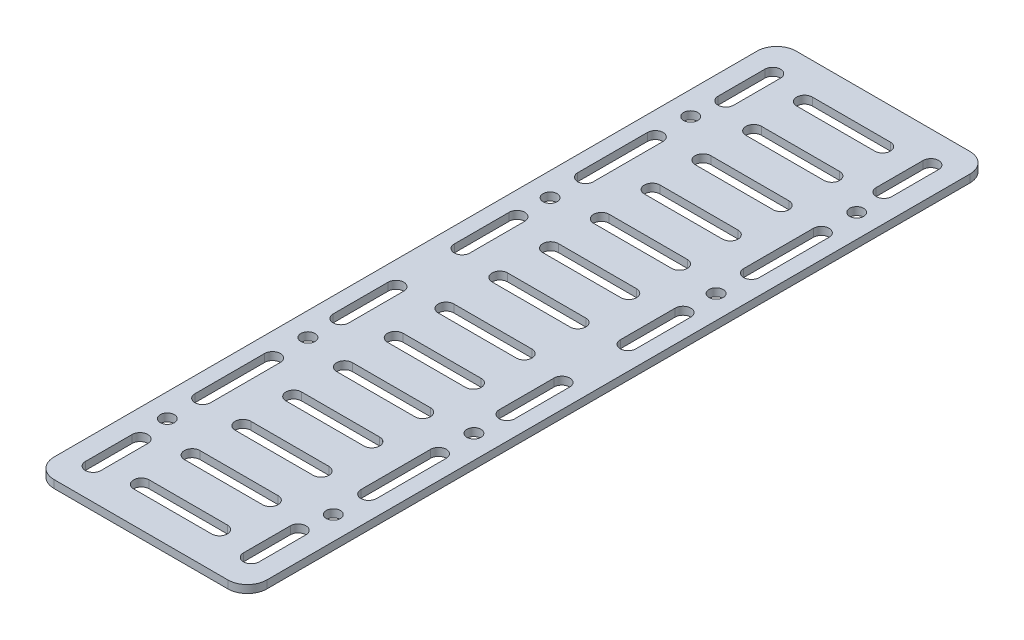
SolidWorks part; units mm, degrees
ref_plane "Front Plane" through (0, 0, 0) normal (0, 0, 1) x (1, 0, 0)
ref_plane "Top Plane" through (0, 0, 0) normal (0, 1, 0) x (1, 0, 0)
ref_plane "Right Plane" through (0, 0, 0) normal (1, 0, 0) x (0, 0, -1)
sketch "Sketch1" plane through (0, 0, 0) normal (0, 1, 0) x (1, 0, 0)
  line L1 (-27.25, 95) -> (27.25, 95)
  line L2 (-27.25, 95) -> (-27.25, -95)
  line L3 (-27.25, -95) -> (27.25, -95)
  line L4 (27.25, 95) -> (27.25, -95)
  line L5 (-27.25, 95) -> (27.25, -95) construction
  line L6 (-27.25, -95) -> (27.25, 95) construction
  point P0 (0, 0)
  dimension "D1" = 54.5
  dimension "D2" = 190
extrude "Boss-Extrude1" add sketch "Sketch1" along normal blind 2
hole_wizard "M3 Clearance Hole1" positions "Sketch3" profile "Sketch4" hole size "M3" standard "ANSI Metric" end condition through all
sketch "Sketch3" plane through (0, 2, 0) normal (0, 1, 0) x (1, 0, 0)
  line L0 (0, 0) -> (0, 100.7242) construction
  line L2 (0, 0) -> (-58.9219, 0) construction
  line L4 (-27.25, 95) -> (-27.25, -95) construction
  point P0 (-21.25, 67)
  point P15 (-21.25, 31)
  point P17 (21.25, 67)
  point P18 (21.25, 31)
  point P20 (21.25, -31)
  point P21 (21.25, -67)
  point P22 (-21.25, -67)
  point P23 (-21.25, -31)
  dimension "D1" = 6
  dimension "D2" = 31
  dimension "D3" = 36
sketch "Sketch4" plane through (-21.25, 2, -67) normal (1, 0, 0) x (0, 0, 1)
  line L0 (0, 0) -> (0, 2)
  line L1 (0, 2) -> (1.8, 2)
  line L2 (1.8, 2) -> (1.8, 0)
  line L5 (1.8, 0) -> (0, 0)
  line L11 (0, -6.35) -> (0, 107.95) construction
  dimension "Thru Hole Dia." = 3.6
  dimension "Thru Hole Depth" = 2
sketch "Sketch5" plane through (0, 2, 0) normal (0, 1, 0) x (1, 0, 0)
  line L0 (-20.25, 87) -> (-20.25, 75) construction
  line L1 (-18.25, 87) -> (-18.25, 75)
  line L2 (-22.25, 87) -> (-22.25, 75)
  line L3 (0, 0) -> (0, 101.9957) construction
  line L4 (20.25, 87) -> (20.25, 75) construction
  line L5 (18.25, 87) -> (18.25, 75)
  line L6 (22.25, 87) -> (22.25, 75)
  line L11 (-10, 84.8852) -> (10, 84.8852) construction
  line L12 (-10, 86.8852) -> (10, 86.8852)
  line L13 (-10, 82.8852) -> (10, 82.8852)
  line L14 (-10, 71.8852) -> (10, 71.8852) construction
  line L15 (-10, 73.8852) -> (10, 73.8852)
  line L16 (-10, 69.8852) -> (10, 69.8852)
  line L17 (-10, 58.8852) -> (10, 58.8852) construction
  line L18 (-10, 60.8852) -> (10, 60.8852)
  line L19 (-10, 56.8852) -> (10, 56.8852)
  line L20 (-10, 45.8852) -> (10, 45.8852) construction
  line L21 (-10, 47.8852) -> (10, 47.8852)
  line L22 (-10, 43.8852) -> (10, 43.8852)
  line L23 (-10, 32.8852) -> (10, 32.8852) construction
  line L24 (-10, 34.8852) -> (10, 34.8852)
  line L25 (-10, 30.8852) -> (10, 30.8852)
  line L26 (-10, 19.8852) -> (10, 19.8852) construction
  line L27 (-10, 21.8852) -> (10, 21.8852)
  line L28 (-10, 17.8852) -> (10, 17.8852)
  line L29 (-10, 6.8852) -> (10, 6.8852) construction
  line L30 (-10, 8.8852) -> (10, 8.8852)
  line L31 (-10, 4.8852) -> (10, 4.8852)
  line L32 (-21.25, 67) -> (-21.25, 31) construction
  line L33 (-21.25, 57.9327) -> (-21.25, 40.0673) construction
  line L34 (-19.25, 57.9327) -> (-19.25, 40.0673)
  line L35 (-23.25, 57.9327) -> (-23.25, 40.0673)
  line L36 (-21.25, 31) -> (-21.25, 0) construction
  line L37 (-21.25, 22.5337) -> (-21.25, 8.4663) construction
  line L38 (-19.25, 22.5337) -> (-19.25, 8.4663)
  line L39 (-23.25, 22.5337) -> (-23.25, 8.4663)
  line L40 (21.25, 57.9327) -> (21.25, 40.0673) construction
  line L41 (19.25, 57.9327) -> (19.25, 40.0673)
  line L42 (23.25, 57.9327) -> (23.25, 40.0673)
  line L43 (21.25, 22.5337) -> (21.25, 8.4663) construction
  line L44 (19.25, 22.5337) -> (19.25, 8.4663)
  line L45 (23.25, 22.5337) -> (23.25, 8.4663)
  line L46 (0, 0) -> (46.6314, 0) construction
  line L47 (-20.25, -87) -> (-20.25, -75) construction
  line L48 (-18.25, -87) -> (-18.25, -75)
  line L49 (-22.25, -87) -> (-22.25, -75)
  line L50 (20.25, -87) -> (20.25, -75) construction
  line L51 (18.25, -87) -> (18.25, -75)
  line L52 (22.25, -87) -> (22.25, -75)
  line L56 (-10, -84.8852) -> (10, -84.8852) construction
  line L57 (-10, -86.8852) -> (10, -86.8852)
  line L58 (-10, -82.8852) -> (10, -82.8852)
  line L59 (-10, -71.8852) -> (10, -71.8852) construction
  line L60 (-10, -73.8852) -> (10, -73.8852)
  line L61 (-10, -69.8852) -> (10, -69.8852)
  line L62 (-10, -58.8852) -> (10, -58.8852) construction
  line L63 (-10, -60.8852) -> (10, -60.8852)
  line L64 (-10, -56.8852) -> (10, -56.8852)
  line L65 (-10, -45.8852) -> (10, -45.8852) construction
  line L66 (-10, -47.8852) -> (10, -47.8852)
  line L67 (-10, -43.8852) -> (10, -43.8852)
  line L68 (-10, -32.8852) -> (10, -32.8852) construction
  line L69 (-10, -34.8852) -> (10, -34.8852)
  line L70 (-10, -30.8852) -> (10, -30.8852)
  line L71 (-10, -19.8852) -> (10, -19.8852) construction
  line L72 (-10, -21.8852) -> (10, -21.8852)
  line L73 (-10, -17.8852) -> (10, -17.8852)
  line L74 (-10, -6.8852) -> (10, -6.8852) construction
  line L75 (-10, -8.8852) -> (10, -8.8852)
  line L76 (-10, -4.8852) -> (10, -4.8852)
  line L77 (-21.25, -57.9327) -> (-21.25, -40.0673) construction
  line L78 (-19.25, -57.9327) -> (-19.25, -40.0673)
  line L79 (-23.25, -57.9327) -> (-23.25, -40.0673)
  line L80 (-21.25, -22.5337) -> (-21.25, -8.4663) construction
  line L81 (-19.25, -22.5337) -> (-19.25, -8.4663)
  line L82 (-23.25, -22.5337) -> (-23.25, -8.4663)
  line L83 (21.25, -57.9327) -> (21.25, -40.0673) construction
  line L84 (19.25, -57.9327) -> (19.25, -40.0673)
  line L85 (23.25, -57.9327) -> (23.25, -40.0673)
  line L86 (21.25, -22.5337) -> (21.25, -8.4663) construction
  line L87 (19.25, -22.5337) -> (19.25, -8.4663)
  line L88 (23.25, -22.5337) -> (23.25, -8.4663)
  arc A0 (-18.25, 87) -> (-22.25, 87) centre (-20.25, 87) ccw
  arc A1 (-22.25, 75) -> (-18.25, 75) centre (-20.25, 75) ccw
  arc A2 (18.25, 87) -> (22.25, 87) centre (20.25, 87) cw
  arc A3 (22.25, 75) -> (18.25, 75) centre (20.25, 75) cw
  arc A6 (-10, 86.8852) -> (-10, 82.8852) centre (-10, 84.8852) ccw
  arc A7 (10, 82.8852) -> (10, 86.8852) centre (10, 84.8852) ccw
  arc A8 (-10, 73.8852) -> (-10, 69.8852) centre (-10, 71.8852) ccw
  arc A9 (10, 69.8852) -> (10, 73.8852) centre (10, 71.8852) ccw
  arc A10 (-10, 60.8852) -> (-10, 56.8852) centre (-10, 58.8852) ccw
  arc A11 (10, 56.8852) -> (10, 60.8852) centre (10, 58.8852) ccw
  arc A12 (-10, 47.8852) -> (-10, 43.8852) centre (-10, 45.8852) ccw
  arc A13 (10, 43.8852) -> (10, 47.8852) centre (10, 45.8852) ccw
  arc A14 (-10, 34.8852) -> (-10, 30.8852) centre (-10, 32.8852) ccw
  arc A15 (10, 30.8852) -> (10, 34.8852) centre (10, 32.8852) ccw
  arc A16 (-10, 21.8852) -> (-10, 17.8852) centre (-10, 19.8852) ccw
  arc A17 (10, 17.8852) -> (10, 21.8852) centre (10, 19.8852) ccw
  arc A18 (-10, 8.8852) -> (-10, 4.8852) centre (-10, 6.8852) ccw
  arc A19 (10, 4.8852) -> (10, 8.8852) centre (10, 6.8852) ccw
  arc A20 (-19.25, 57.9327) -> (-23.25, 57.9327) centre (-21.25, 57.9327) ccw
  arc A21 (-23.25, 40.0673) -> (-19.25, 40.0673) centre (-21.25, 40.0673) ccw
  arc A22 (-19.25, 22.5337) -> (-23.25, 22.5337) centre (-21.25, 22.5337) ccw
  arc A23 (-23.25, 8.4663) -> (-19.25, 8.4663) centre (-21.25, 8.4663) ccw
  arc A24 (19.25, 57.9327) -> (23.25, 57.9327) centre (21.25, 57.9327) cw
  arc A25 (23.25, 40.0673) -> (19.25, 40.0673) centre (21.25, 40.0673) cw
  arc A26 (19.25, 22.5337) -> (23.25, 22.5337) centre (21.25, 22.5337) cw
  arc A27 (23.25, 8.4663) -> (19.25, 8.4663) centre (21.25, 8.4663) cw
  arc A28 (-18.25, -87) -> (-22.25, -87) centre (-20.25, -87) cw
  arc A29 (-22.25, -75) -> (-18.25, -75) centre (-20.25, -75) cw
  arc A30 (18.25, -87) -> (22.25, -87) centre (20.25, -87) ccw
  arc A31 (22.25, -75) -> (18.25, -75) centre (20.25, -75) ccw
  arc A34 (-10, -86.8852) -> (-10, -82.8852) centre (-10, -84.8852) cw
  arc A35 (10, -82.8852) -> (10, -86.8852) centre (10, -84.8852) cw
  arc A36 (-10, -73.8852) -> (-10, -69.8852) centre (-10, -71.8852) cw
  arc A37 (10, -69.8852) -> (10, -73.8852) centre (10, -71.8852) cw
  arc A38 (-10, -60.8852) -> (-10, -56.8852) centre (-10, -58.8852) cw
  arc A39 (10, -56.8852) -> (10, -60.8852) centre (10, -58.8852) cw
  arc A40 (-10, -47.8852) -> (-10, -43.8852) centre (-10, -45.8852) cw
  arc A41 (10, -43.8852) -> (10, -47.8852) centre (10, -45.8852) cw
  arc A42 (-10, -34.8852) -> (-10, -30.8852) centre (-10, -32.8852) cw
  arc A43 (10, -30.8852) -> (10, -34.8852) centre (10, -32.8852) cw
  arc A44 (-10, -21.8852) -> (-10, -17.8852) centre (-10, -19.8852) cw
  arc A45 (10, -17.8852) -> (10, -21.8852) centre (10, -19.8852) cw
  arc A46 (-10, -8.8852) -> (-10, -4.8852) centre (-10, -6.8852) cw
  arc A47 (10, -4.8852) -> (10, -8.8852) centre (10, -6.8852) cw
  arc A48 (-19.25, -57.9327) -> (-23.25, -57.9327) centre (-21.25, -57.9327) cw
  arc A49 (-23.25, -40.0673) -> (-19.25, -40.0673) centre (-21.25, -40.0673) cw
  arc A50 (-19.25, -22.5337) -> (-23.25, -22.5337) centre (-21.25, -22.5337) cw
  arc A51 (-23.25, -8.4663) -> (-19.25, -8.4663) centre (-21.25, -8.4663) cw
  arc A52 (19.25, -57.9327) -> (23.25, -57.9327) centre (21.25, -57.9327) ccw
  arc A53 (23.25, -40.0673) -> (19.25, -40.0673) centre (21.25, -40.0673) ccw
  arc A54 (19.25, -22.5337) -> (23.25, -22.5337) centre (21.25, -22.5337) ccw
  arc A55 (23.25, -8.4663) -> (19.25, -8.4663) centre (21.25, -8.4663) ccw
  point P2 (-20.25, 81)
  point P12 (20.25, 81)
  point P29 (0, 84.8852)
  point P36 (0, 71.8852)
  point P43 (0, 58.8852)
  point P50 (0, 45.8852)
  point P57 (0, 32.8852)
  point P64 (0, 19.8852)
  point P71 (0, 6.8852)
  point P81 (-21.25, 49)
  point P89 (-21.25, 15.5)
  point P96 (21.25, 49)
  point P103 (21.25, 15.5)
  point P111 (-20.25, -81)
  point P118 (20.25, -81)
  point P132 (0, -84.8852)
  point P139 (0, -71.8852)
  point P146 (0, -58.8852)
  point P153 (0, -45.8852)
  point P160 (0, -32.8852)
  point P167 (0, -19.8852)
  point P174 (0, -6.8852)
  point P181 (-21.25, -49)
  point P188 (-21.25, -15.5)
  point P195 (21.25, -49)
  point P202 (21.25, -15.5)
  dimension "D1" = 4
  dimension "D2" = 36.5
  dimension "D3" = 75
  dimension "D4" = 12
  dimension "D8" = 4
  dimension "D9" = 4
extrude "Cut-Extrude1" cut sketch "Sketch5" against normal through all
fillet "Fillet1" radius 5 4 edges at (-27.25, 1, -95) (27.25, 1, -95) (-27.25, 1, 95) (27.25, 1, 95)
